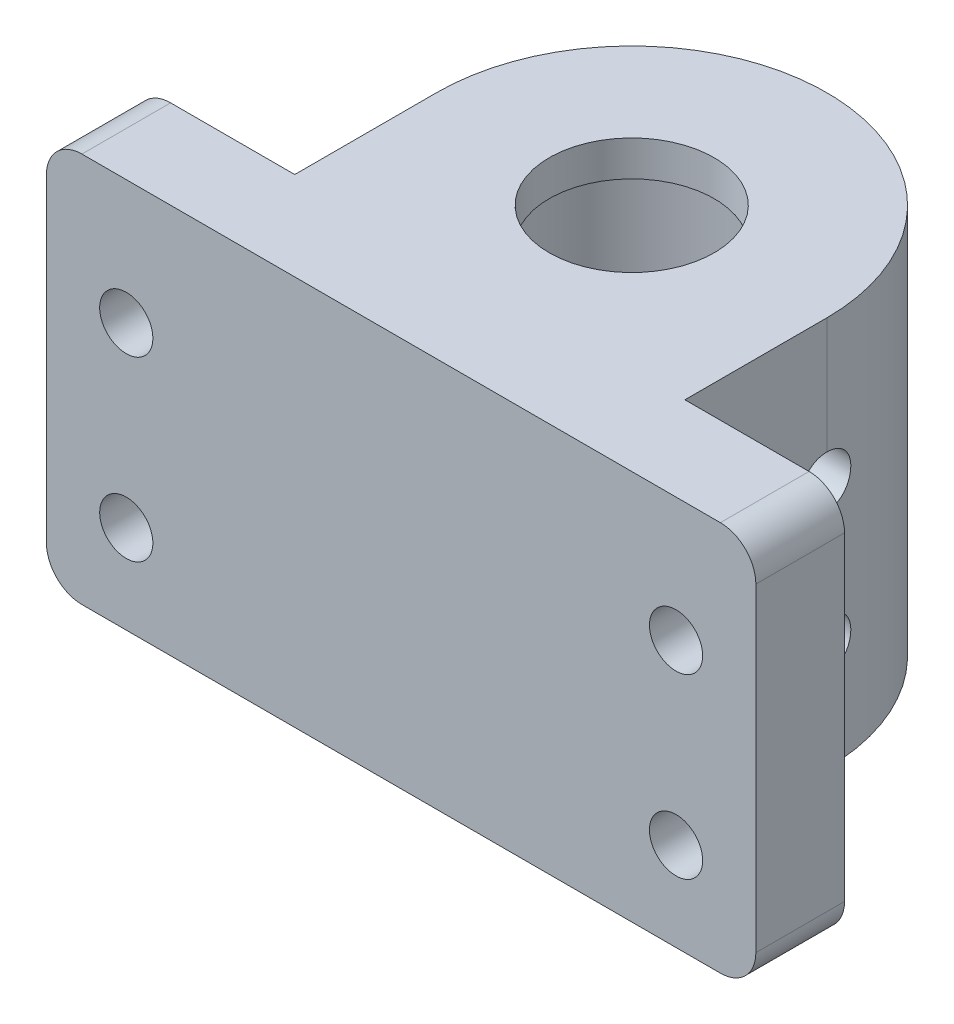
SolidWorks part; units mm, degrees
ref_plane "前视基准面" through (0, 0, 0) normal (0, 0, 1) x (1, 0, 0)
ref_plane "上视基准面" through (0, 0, 0) normal (0, 1, 0) x (1, 0, 0)
ref_plane "右视基准面" through (0, 0, 0) normal (1, 0, 0) x (0, 0, -1)
sketch "草图1" plane through (0, 0, 0) normal (0, 1, 0) x (1, 0, 0)
  line L0 (0, 0) -> (0, -10.5) construction
  line L1 (-11, 0) -> (-11, -8)
  line L2 (-20, -13) -> (20, -13)
  line L3 (-20, -13) -> (-20, -8)
  line L4 (-20, -8) -> (20, -8) construction
  line L5 (20, -13) -> (20, -8)
  line L6 (-20, -13) -> (20, -8) construction
  line L7 (-20, -8) -> (20, -13) construction
  line L8 (-11, -8) -> (-20, -8)
  line L9 (11, 0) -> (11, -8)
  line L10 (11, -8) -> (20, -8)
  circle A0 centre (0, 0) radius 6.65
  arc A1 (11, 0) -> (-11, 0) centre (0, 0) ccw
  dimension "D1" = 13.3
  dimension "D4" = 11
  dimension "D2" = 5
  dimension "D3" = 13
  dimension "D5" = 40
extrude "凸台-拉伸1" add sketch "草图1" along normal blind 20
sketch "草图2" plane through (0, 0, 8) normal (0, 0, -1) x (-1, 0, 0)
  line L0 (20, 10) -> (-20, 10) construction
  line L1 (20, 20) -> (20, 0) construction
  line L2 (-20, 20) -> (-20, 0) construction
  line L3 (15.5, 0) -> (15.5, 20) construction
  line L4 (11, 0) -> (20, 0) construction
  line L5 (11, 20) -> (20, 20) construction
  line L6 (0, 0) -> (0, 20) construction
  line L7 (-11, 0) -> (11, 0) construction
  line L8 (11, 20) -> (-11, 20) construction
  circle A0 centre (15.5, 5) radius 1.5
  circle A1 centre (15.5, 15) radius 1.5
  circle A2 centre (-15.5, 15) radius 1.5
  circle A3 centre (-15.5, 5) radius 1.5
  dimension "D1" = 3
  dimension "D2" = 10
extrude "切除-拉伸1" cut sketch "草图2" against normal through all
ref_plane "基准面1" through (0, 0, -11) normal (0, 0, -1) x (-1, 0, 0)
sketch "草图3" plane through (0, 0, -11) normal (0, 0, -1) x (-1, 0, 0)
  line L0 (0, 0) -> (0, 20) construction
  line L1 (-11, 0) -> (11, 0) construction
  line L2 (11, 20) -> (-11, 20) construction
  circle A0 centre (0, 6) radius 1.45
  circle A1 centre (0, 14) radius 1.45
  dimension "D1" = 2.9
  dimension "D2" = 6
  dimension "D3" = 2.9
  dimension "D4" = 8
extrude "切除-拉伸2" cut sketch "草图3" against normal blind 10
pattern_circular "阵列(圆周)1" count 2 every 90 about axis through (0, 20, 0) along (0, -1, 0) of "切除-拉伸2"
sketch "草图4" plane through (0, 20, 0) normal (0, 1, 0) x (1, 0, 0)
  line L7 (20, -8) -> (11, -8)
  line L8 (11, -8) -> (11, 0)
  line L9 (-11, 0) -> (-11, -8)
  line L10 (-11, -8) -> (-20, -8)
  line L11 (-20, -8) -> (-20, -13)
  line L12 (-20, -13) -> (20, -13)
  line L13 (20, -13) -> (20, -8)
  line L14 (20, -8) -> (11, -8)
  line L15 (11, -8) -> (11, 0)
  line L16 (-11, 0) -> (-11, -8)
  line L17 (-11, -8) -> (-20, -8)
  line L18 (-20, -8) -> (-20, -13)
  line L19 (-20, -13) -> (20, -13)
  line L20 (20, -13) -> (20, -8)
  circle A0 centre (0, 0) radius 4.65
  arc A1 (11, 0) -> (-11, 0) centre (0, 0) ccw
  arc A2 (11, 0) -> (-11, 0) centre (0, 0) ccw
  circle A3 centre (0, 0) radius 6.65 construction
  dimension "D2" = 2
  dimension "D1" = 0
extrude "凸台-拉伸2" add sketch "草图4" along normal blind 2
fillet "圆角1" radius 2 4 edges at (-20, 22, 10.5) (-20, 0, 10.5) (20, 0, 10.5) (20, 22, 10.5)
